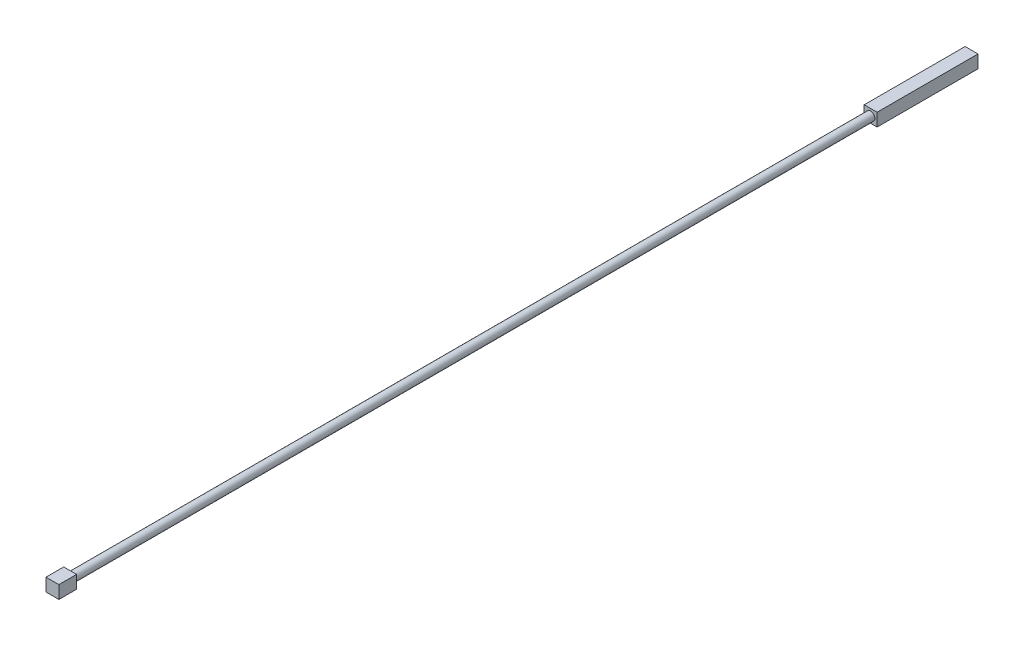
SolidWorks part; units mm, degrees
ref_plane "Front Plane" through (0, 0, 0) normal (0, 0, 1) x (1, 0, 0)
ref_plane "Top Plane" through (0, 0, 0) normal (0, 1, 0) x (1, 0, 0)
ref_plane "Right Plane" through (0, 0, 0) normal (1, 0, 0) x (0, 0, -1)
sketch "Sketch1" plane through (0, 0, 0) normal (0, 0, 1) x (1, 0, 0)
  circle A0 centre (0, 0) radius 5
  dimension "D1" = 10
extrude "Boss-Extrude1" add sketch "Sketch1" along normal blind 1069.975
sketch "Sketch2" plane through (0, 0, 0) normal (0, 0, 1) x (1, 0, 0)
  line L1 (7.5, 7.5) -> (-7.5, 7.5)
  line L2 (7.5, 7.5) -> (7.5, -7.5)
  line L3 (7.5, -7.5) -> (-7.5, -7.5)
  line L4 (-7.5, 7.5) -> (-7.5, -7.5)
  line L5 (7.5, 7.5) -> (-7.5, -7.5) construction
  line L6 (7.5, -7.5) -> (-7.5, 7.5) construction
  point P0 (0, 0)
  dimension "D1" = 15
  dimension "D2" = 15
extrude "Boss-Extrude2" add sketch "Sketch2" along normal blind 117.475
sketch "Sketch3" plane through (0, 0, 1069.975) normal (0, 0, 1) x (1, 0, 0)
  line L4 (-7.5, 7.5) -> (-7.5, -7.5)
  line L5 (-7.5, -7.5) -> (7.5, -7.5)
  line L6 (7.5, -7.5) -> (7.5, 7.5)
  line L7 (7.5, 7.5) -> (-7.5, 7.5)
  line L8 (-7.5, 7.5) -> (-7.5, -7.5)
  line L9 (-7.5, -7.5) -> (7.5, -7.5)
  line L10 (7.5, -7.5) -> (7.5, 7.5)
  line L11 (7.5, 7.5) -> (-7.5, 7.5)
  dimension "D1" = 0
extrude "Boss-Extrude3" add sketch "Sketch3" against normal blind 20.6375
